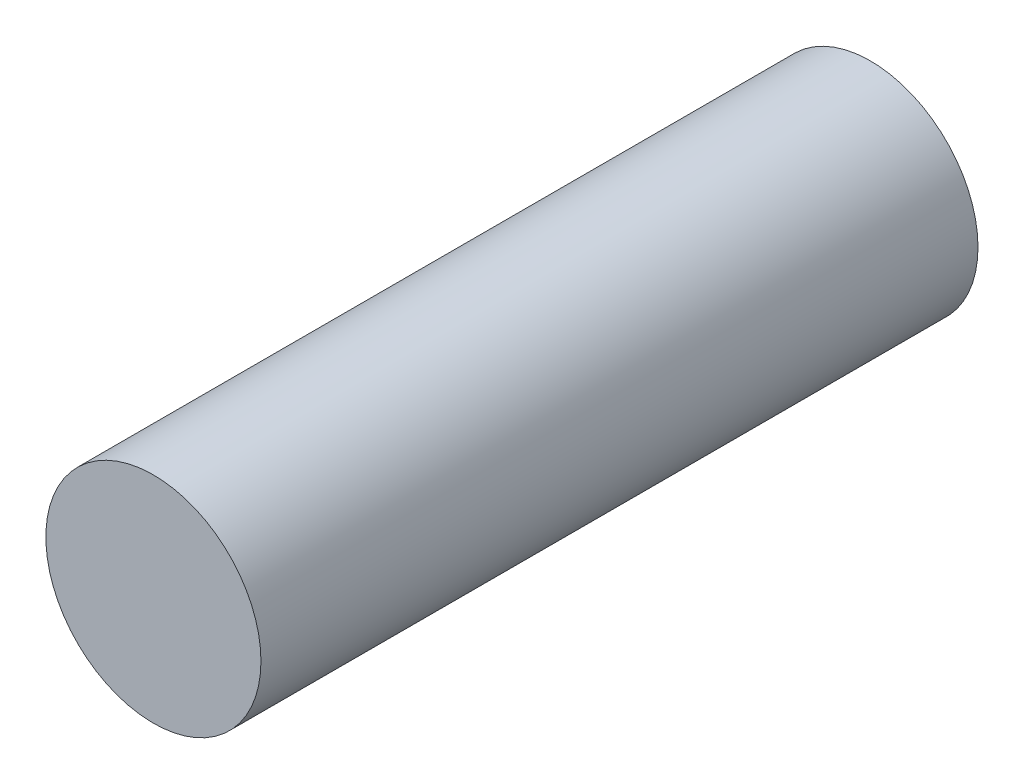
SolidWorks part; units mm, degrees
ref_plane "Front Plane" through (0, 0, 0) normal (0, 0, 1) x (1, 0, 0)
ref_plane "Top Plane" through (0, 0, 0) normal (0, 1, 0) x (1, 0, 0)
ref_plane "Right Plane" through (0, 0, 0) normal (1, 0, 0) x (0, 0, -1)
sketch "Sketch1" plane through (0, 0, 0) normal (0, 0, 1) x (1, 0, 0)
  circle A0 centre (0, 0) radius 9
  dimension "D1" = 18
extrude "Boss-Extrude1" add sketch "Sketch1" along normal blind 60
